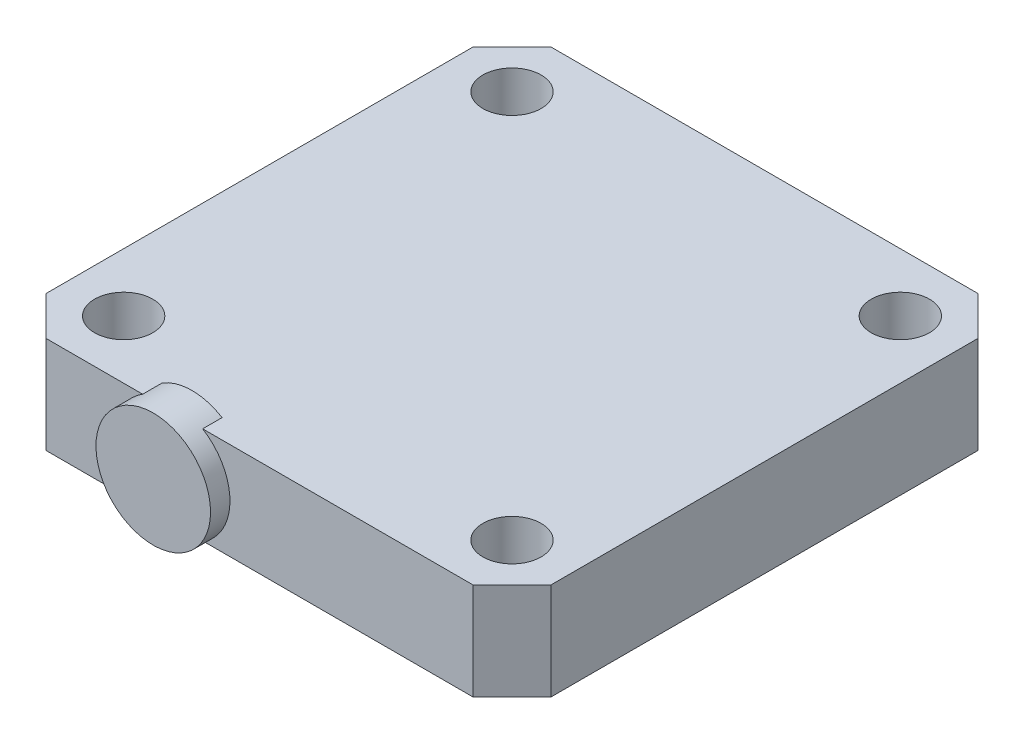
SolidWorks part; units mm, degrees
ref_plane "Front Plane" through (0, 0, 0) normal (0, 0, 1) x (1, 0, 0)
ref_plane "Top Plane" through (0, 0, 0) normal (0, 1, 0) x (1, 0, 0)
ref_plane "Right Plane" through (0, 0, 0) normal (1, 0, 0) x (0, 0, -1)
sketch "Sketch1" plane through (0, 0, 0) normal (0, 1, 0) x (1, 0, 0)
  line L0 (-11, 13) -> (-13, 11)
  line L1 (11, -13) -> (-11, -13)
  line L2 (13, -11) -> (13, 11)
  line L3 (11, 13) -> (-11, 13)
  line L4 (-13, -11) -> (-13, 11)
  line L5 (13, -13) -> (-13, 13) construction
  line L6 (13, 13) -> (-13, -13) construction
  line L7 (10, -10) -> (-10, -10) construction
  line L8 (10, -10) -> (10, 10) construction
  line L9 (10, 10) -> (-10, 10) construction
  line L10 (-10, -10) -> (-10, 10) construction
  line L11 (10, -10) -> (-10, 10) construction
  line L12 (10, 10) -> (-10, -10) construction
  line L13 (13, 11) -> (11, 13)
  line L14 (13, -11) -> (11, -13)
  line L15 (-11, -13) -> (-13, -11)
  circle A0 centre (-10, 10) radius 1.5
  circle A1 centre (10, 10) radius 1.5
  circle A2 centre (10, -10) radius 1.5
  circle A3 centre (-10, -10) radius 1.5
  point P0 (0, 0)
  point P6 (0, 0)
  dimension "D1" = 26
  dimension "D2" = 26
  dimension "D3" = 20
  dimension "D4" = 20
extrude "Boss-Extrude1" add sketch "Sketch1" along normal blind 5
sketch "Sketch2" plane through (0, 0, 13) normal (0, 0, 1) x (1, 0, 0)
  circle A1 centre (-4.4763, 2.4862) radius 2.9503
extrude "Boss-Extrude2" add sketch "Sketch2" along normal mid plane 2
sketch "Sketch3" plane through (0, 0, 14) normal (0, 0, 1) x (1, 0, 0)
  circle A0 centre (-4.4763, 2.3895) radius 1.6452
sketch "Sketch25" plane through (0, 0, 0) normal (1, 0, 0) x (0, 0, -1)
  line L0 (-14, 4.0346) -> (-14, 0.7443) construction
  spline S0 degree 2 poles (-14, 2.3895) (-39.1923, 16.8936) (-40.9005, 42.0027) knots 0 0 0 1 1 1
sweep "Sweep5" [suppressed] add profiles "Sketch3" path "Sketch25"
ref_plane "Plane2" through (0, 45, 0) normal (0, 1, 0) x (1, 0, 0)
sketch "Sketch30" plane through (0, 45, 0) normal (0, 1, 0) x (1, 0, 0)
  circle A0 centre (-4.4763, -40.9005) radius 2.2104
extrude "Boss-Extrude4" [suppressed] add sketch "Sketch30" against normal blind 4
